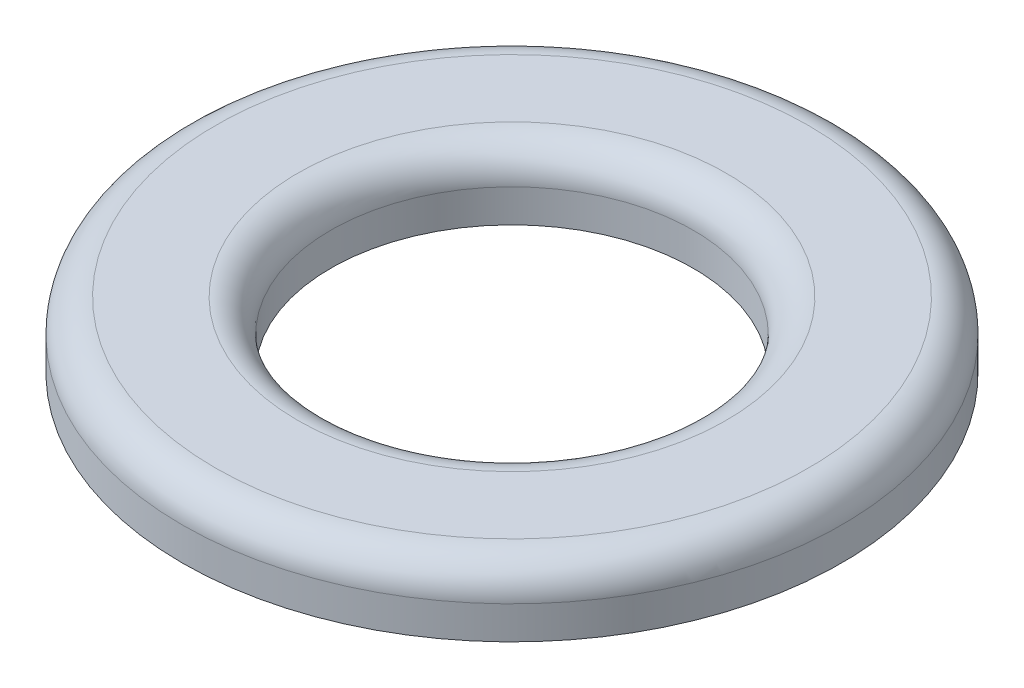
SolidWorks part; units mm, degrees
ref_plane "Front Plane" through (0, 0, 0) normal (0, 0, 1) x (1, 0, 0)
ref_plane "Top Plane" through (0, 0, 0) normal (0, 1, 0) x (1, 0, 0)
ref_plane "Right Plane" through (0, 0, 0) normal (1, 0, 0) x (0, 0, -1)
sketch "Sketch1" plane through (0, 0, 0) normal (0, 1, 0) x (1, 0, 0)
  circle A0 centre (0, 0) radius 50
  circle A1 centre (0, 0) radius 27.5
extrude "Boss-Extrude1" add sketch "Sketch1" along normal blind 10
fillet "Fillet1" radius 5 2 edges at (0, 10, 27.5) (0, 10, 50)
sketch "Sketch2" plane through (0, 0, 0) normal (0, -1, 0) x (1, 0, 0)
  circle A0 centre (0, 0) radius 40
  circle A1 centre (0, 0) radius 43
extrude "Boss-Extrude2" add sketch "Sketch2" along normal blind 3
